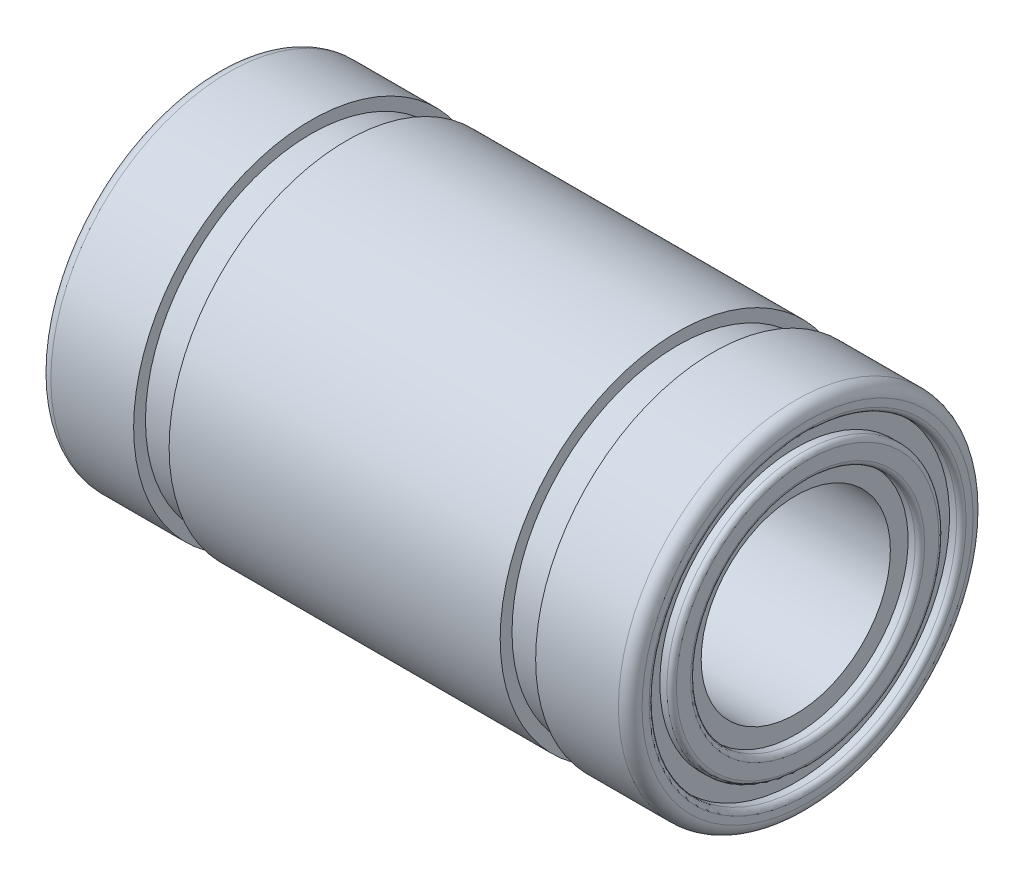
SolidWorks part; units mm, degrees
ref_plane "Front Plane" through (0, 0, 0) normal (0, 0, 1) x (1, 0, 0)
ref_plane "Top Plane" through (0, 0, 0) normal (0, 1, 0) x (1, 0, 0)
ref_plane "Right Plane" through (0, 0, 0) normal (1, 0, 0) x (0, 0, -1)
sketch "Sketch1" plane through (0, 0, 0) normal (0, 0, 1) x (1, 0, 0)
  line L0 (25, 6.5) -> (24.5, 6.5)
  line L1 (0, 0) -> (25, 0)
  line L2 (0, 0) -> (0, 4)
  line L3 (0, 7.5) -> (4, 7.5)
  line L4 (25, 0) -> (25, 4)
  line L5 (24.5, 6.5) -> (24.5, 5.75)
  line L6 (24.5, 5.75) -> (25, 5.75)
  line L7 (25, 6.5) -> (25, 7.5)
  line L8 (25, 4.75) -> (24.5, 4.75)
  line L9 (24.5, 4.75) -> (24.5, 4)
  line L10 (24.5, 4) -> (25, 4)
  line L11 (25, 4.75) -> (25, 5.75)
  line L12 (12.5, 7.5) -> (12.5, 0) construction
  line L13 (0.5, 4) -> (0, 4)
  line L14 (0.5, 4.75) -> (0.5, 4)
  line L15 (0, 4.75) -> (0.5, 4.75)
  line L16 (0.5, 5.75) -> (0, 5.75)
  line L17 (0.5, 6.5) -> (0.5, 5.75)
  line L18 (0, 6.5) -> (0.5, 6.5)
  line L19 (0, 6.5) -> (0, 7.5)
  line L20 (0, 4.75) -> (0, 5.75)
  line L21 (4, 7.5) -> (4, 7)
  line L22 (4, 7) -> (5.5, 7)
  line L23 (5.5, 7) -> (5.5, 7.5)
  line L24 (21, 7.5) -> (21, 7)
  line L25 (19.5, 7) -> (19.5, 7.5)
  line L26 (21, 7) -> (19.5, 7)
  line L27 (5.5, 7.5) -> (19.5, 7.5)
  line L28 (21, 7.5) -> (25, 7.5)
  dimension "D1" = 25
  dimension "D2" = 7.5
  dimension "D3" = 4
  dimension "D4" = 0.75
  dimension "D5" = 0.75
  dimension "D6" = 1
  dimension "D7" = 0.5
  dimension "D8" = 0.5
  dimension "D9" = 4
  dimension "D10" = 1.5
  dimension "D11" = 0.5
revolve "Revolve1" add sketch "Sketch1" angle 360 about L1
sketch "Sketch2" plane through (25, 0, 0) normal (1, 0, 0) x (0, 0, -1)
  circle A0 centre (0, 0) radius 4
extrude "Cut-Extrude1" cut sketch "Sketch2" against normal blind 52
fillet "Fillet1" radius 0.5 2 edges at (25, 0, 7.5) (0, 0, 7.5)
fillet "Fillet2" radius 0.2 6 edges at (0, 0, 4.75) (0, 0, 5.75) (25, 0, 4.75) (25, 0, 5.75) (0, 0, 6.5) (25, 0, 6.5)
